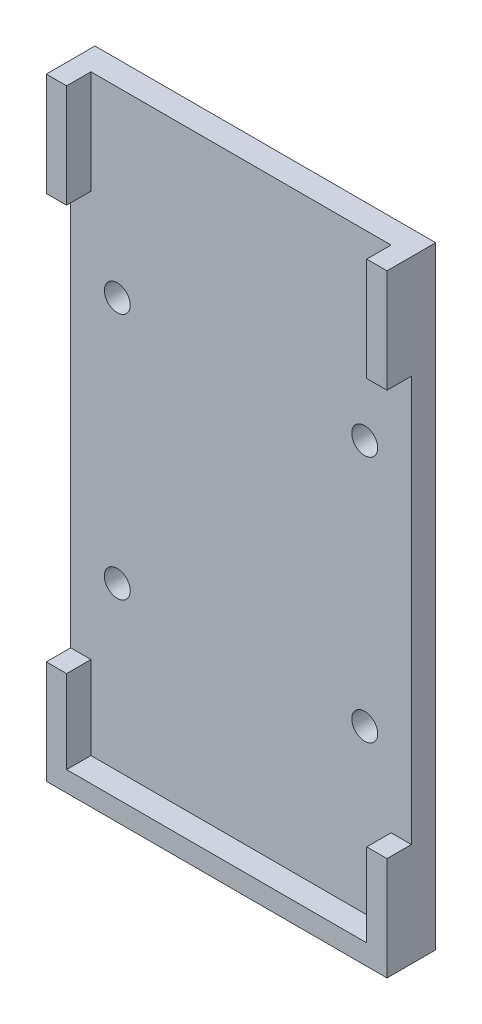
SolidWorks part; units mm, degrees
ref_plane "Front Plane" through (0, 0, 0) normal (0, 0, 1) x (1, 0, 0)
ref_plane "Top Plane" through (0, 0, 0) normal (0, 1, 0) x (1, 0, 0)
ref_plane "Right Plane" through (0, 0, 0) normal (1, 0, 0) x (0, 0, -1)
sketch "Sketch1" plane through (0, 0, 0) normal (0, 0, 1) x (1, 0, 0)
  line L1 (0, 0) -> (37, 0)
  line L2 (0, 0) -> (0, 73)
  line L4 (37, 0) -> (37, 73)
  point P5 (0, 73)
  point P6 (0, 0)
  point P7 (0, 0)
  dimension "D1" = 37
  dimension "D2" = 73
extrude "Extrude-Thin1" add sketch "Sketch1" along normal blind 3 thin
sketch "Sketch2" plane through (0, 0, 0) normal (0, 0, -1) x (-1, 0, 0)
  line L0 (-39.5, 73) -> (2.5, 73)
  line L4 (0, 73) -> (0, 0)
  line L5 (-37, 73) -> (-39.5, 73)
  line L6 (-37, 0) -> (-37, 73)
  line L7 (0, 0) -> (-37, 0)
  line L17 (-39.5, 73) -> (-39.5, -2.5)
  line L18 (-39.5, 73) -> (-39.5, -2.5)
  line L19 (-39.5, -2.5) -> (2.5, -2.5)
  line L20 (-39.5, -2.5) -> (2.5, -2.5)
  line L21 (2.5, -2.5) -> (2.5, 73)
  line L22 (2.5, -2.5) -> (2.5, 73)
  line L23 (2.5, 73) -> (0, 73)
  dimension "D1" = 0
extrude "Boss-Extrude2" add sketch "Sketch2" along normal blind 3
sketch "Sketch3" plane through (0, 0, 0) normal (0, 0, 1) x (1, 0, 0)
  line L0 (18.5, -2.5) -> (18.5, 73) construction
  line L1 (39.5, -2.5) -> (-2.5, -2.5) construction
  line L2 (0, 73) -> (37, 73) construction
  line L3 (-2.5, 35.25) -> (39.5, 35.25) construction
  line L4 (-2.5, -2.5) -> (-2.5, 73) construction
  line L5 (39.5, 73) -> (39.5, -2.5) construction
  line L7 (33.75, 50.5) -> (3.25, 50.5) construction
  line L8 (33.75, 50.5) -> (33.75, 20) construction
  line L9 (33.75, 20) -> (3.25, 20) construction
  line L10 (3.25, 50.5) -> (3.25, 20) construction
  line L11 (33.75, 50.5) -> (3.25, 20) construction
  line L12 (33.75, 20) -> (3.25, 50.5) construction
  point P12 (18.5, 35.25)
  dimension "D1" = 30.5
  dimension "D2" = 30.5
hole_wizard "Ø3.2 (3.2) Diameter Hole1" positions "Sketch4" profile "Sketch5" hole size "Ø3.2" standard "ISO" end condition through all
sketch "Sketch4" plane through (0, 0, 0) normal (0, 0, 1) x (1, 0, 0)
  point P0 (3.25, 50.5)
  point P3 (33.75, 50.5)
  point P6 (33.75, 20)
  point P9 (3.25, 20)
sketch "Sketch5" plane through (3.25, 50.5, 0) normal (1, 0, 0) x (0, -1, 0)
  line L0 (0, 0) -> (0, 3)
  line L1 (0, 3) -> (1.6, 3)
  line L2 (1.6, 3) -> (1.6, 0)
  line L5 (1.6, 0) -> (0, 0)
  line L11 (0, -6.35) -> (0, 107.95) construction
  dimension "Thru Hole Dia." = 3.2
  dimension "Thru Hole Depth" = 3
sketch "Sketch6" plane through (0, 0, 3) normal (0, 0, 1) x (1, 0, 0)
  line L0 (-2.5, -2.5) -> (-2.5, 73) construction
  line L1 (-2.5, 10.25) -> (0, 10.25)
  line L2 (-2.5, 10.25) -> (-2.5, 60.25)
  line L3 (-2.5, 60.25) -> (0, 60.25)
  line L4 (0, 10.25) -> (0, 60.25)
  line L5 (0, 0) -> (0, 73) construction
  line L6 (-2.5, 35.25) -> (39.5, 35.25) construction
  point P8 (-2.5, 58.6416)
  point P9 (-2.5, 35.25)
  dimension "D1" = 50
extrude "Cut-Extrude1" cut sketch "Sketch6" against normal up to surface (3 mm away) up to face at (4.85, 50.5, 0)
ref_plane "Plane2" through (18.5, 0, 0) normal (1, 0, 0) x (0, 0, -1)
mirror "Mirror1" about plane through (18.5, 0, 0) normal (1, 0, 0) of "Cut-Extrude1"
